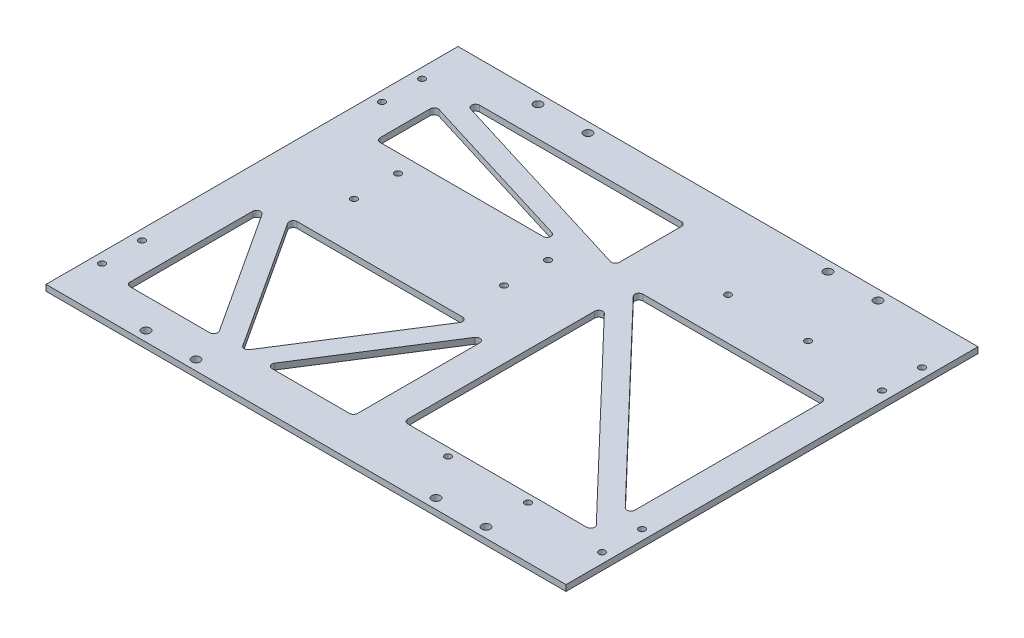
SolidWorks part; units mm, degrees
material "环氧树脂FR-4"
ref_plane "前视基准面" through (0, 0, 0) normal (0, 0, 1) x (1, 0, 0)
ref_plane "上视基准面" through (0, 0, 0) normal (0, 1, 0) x (1, 0, 0)
ref_plane "右视基准面" through (0, 0, 0) normal (1, 0, 0) x (0, 0, -1)
sketch "草图1" plane through (0, 0, 0) normal (0, 1, 0) x (1, 0, 0)
  line L1 (-130, 206) -> (130, 206)
  line L2 (-130, 206) -> (-130, 0)
  line L3 (-130, 0) -> (130, 0)
  line L4 (130, 206) -> (130, 0)
  dimension "D1" = 206
  dimension "D2" = 260
  dimension "D3" = 0
  dimension "D4" = 130
extrude "凸台-拉伸1" add sketch "草图1" along normal blind 3
sketch "草图2" plane through (0, 0, 0) normal (0, -1, 0) x (1, 0, 0)
  line L0 (-130, -206) -> (-130, 0) construction
  line L1 (130, -206) -> (-130, -206) construction
  point P0 (-90, -136)
  point P4 (-15, -136)
  point P7 (-90, -114)
  point P8 (-15, -114)
  dimension "D1" = 40
  dimension "D2" = 70
  dimension "D4" = 75
  dimension "D6" = 22
  dimension "D3" = 2
  dimension "D5" = 2
ref_plane "基准面1" through (0, 0, -103) normal (0, 0, 1) x (1, 0, 0)
hole_wizard "Ø3.2 (3.2) 直径孔1" positions "3D草图1" profile "草图3" hole size "Ø3.2" standard "GB" end condition through all
sketch3d "3D草图1"
  point P0 (-15, 0, -136)
  point P3 (-15, 0, -114)
  point P6 (-90, 0, -136)
  point P9 (-90, 0, -114)
sketch "草图3" plane through (-15, 0, -136) normal (1, 0, 0) x (0, 0, -1)
  line L0 (0, 0) -> (0, 3)
  line L1 (0, 3) -> (1.6, 3)
  line L2 (1.6, 3) -> (1.6, 0)
  line L5 (1.6, 0) -> (0, 0)
  line L11 (0, -6.35) -> (0, 107.95) construction
  dimension "通孔孔直径" = 3.2
  dimension "通孔孔深度" = 3
sketch "草图4" plane through (0, 0, 0) normal (0, -1, 0) x (1, 0, 0)
  line L0 (130, 0) -> (130, -206) construction
  line L1 (130, -206) -> (-130, -206) construction
  point P0 (85, -166)
  point P5 (45, -166)
  point P7 (85, -26)
  point P8 (45, -26)
  dimension "D1" = 45
  dimension "D2" = 40
  dimension "D4" = 40
  dimension "D6" = 140
  dimension "D3" = 2
  dimension "D5" = 2
hole_wizard "Ø3.2 (3.2) 直径孔2" positions "3D草图2" profile "草图5" hole size "Ø3.2" standard "GB" end condition through all
sketch3d "3D草图2"
  point P0 (45, 0, -26)
  point P3 (85, 0, -26)
  point P6 (45, 0, -166)
  point P9 (85, 0, -166)
sketch "草图5" plane through (45, 0, -26) normal (1, 0, 0) x (0, 0, -1)
  line L0 (0, 0) -> (0, 3)
  line L1 (0, 3) -> (1.6, 3)
  line L2 (1.6, 3) -> (1.6, 0)
  line L5 (1.6, 0) -> (0, 0)
  line L11 (0, -6.35) -> (0, 107.95) construction
  dimension "通孔孔直径" = 3.2
  dimension "通孔孔深度" = 3
sketch "草图6" plane through (0, 0, 0) normal (0, -1, 0) x (1, 0, 0)
  line L0 (-130, -206) -> (-130, 0) construction
  line L2 (0, -55) -> (0, 55) construction
  line L4 (1.65, -103) -> (-1.65, -103) construction
  point P0 (-125, -183)
  point P6 (-125, -163)
  point P8 (125, -163)
  point P9 (125, -183)
  point P11 (125, -23)
  point P12 (125, -43)
  point P16 (-125, -43)
  point P17 (-125, -23)
  dimension "D1" = 5
  dimension "D2" = 60
  dimension "D4" = 20
  dimension "D3" = 2
hole_wizard "Ø3.2 (3.2) 直径孔4" positions "3D草图4" profile "草图8" hole size "Ø3.2" standard "GB" end condition through all
sketch3d "3D草图4"
  point P0 (-125, 0, -23)
  point P3 (-125, 0, -43)
  point P6 (-125, 0, -163)
  point P9 (-125, 0, -183)
  point P12 (125, 0, -163)
  point P15 (125, 0, -183)
  point P18 (125, 0, -43)
  point P21 (125, 0, -23)
sketch "草图8" plane through (-125, 0, -23) normal (1, 0, 0) x (0, 0, -1)
  line L0 (0, 0) -> (0, 3)
  line L1 (0, 3) -> (1.6, 3)
  line L2 (1.6, 3) -> (1.6, 0)
  line L5 (1.6, 0) -> (0, 0)
  line L11 (0, -6.35) -> (0, 107.95) construction
  dimension "通孔孔直径" = 3.2
  dimension "通孔孔深度" = 3
sketch "草图9" plane through (0, 0, 0) normal (0, -1, 0) x (1, 0, 0)
  line L0 (130, -206) -> (-130, -206) construction
  point P0 (-60, -201)
  point P3 (-85, -201)
  dimension "D1" = 5
  dimension "D3" = 60
  dimension "D4" = 25
  dimension "D2" = 2
hole_wizard "Ø4.2 (4.2) 直径孔1" positions "3D草图5" profile "草图10" hole size "Ø4.2" standard "GB" end condition through all
sketch3d "3D草图5"
  point P0 (-60, 0, -201)
  point P3 (-85, 0, -201)
sketch "草图10" plane through (-60, 0, -201) normal (1, 0, 0) x (0, 0, -1)
  line L0 (0, 0) -> (0, 3)
  line L1 (0, 3) -> (2.1, 3)
  line L2 (2.1, 3) -> (2.1, 0)
  line L5 (2.1, 0) -> (0, 0)
  line L11 (0, -6.35) -> (0, 107.95) construction
  dimension "通孔孔直径" = 4.2
  dimension "通孔孔深度" = 3
mirror "镜向1" about plane through (0, 0, 0) normal (1, 0, 0) of "Ø4.2 (4.2) 直径孔1"
mirror "镜向2" about plane through (0, 0, -103) normal (0, 0, 1) of "Ø4.2 (4.2) 直径孔1", "镜向1"
sketch "草图11" plane through (0, 0, 0) normal (0, -1, 0) x (1, 0, 0)
  line L0 (-110, -20) -> (-110, -90)
  line L1 (-110, -90) -> (-64.4321, -20)
  line L2 (-64.4321, -20) -> (-110, -20)
  line L3 (-52.5, -20) -> (-98.0679, -90)
  line L4 (-98.0679, -90) -> (-8.0679, -90)
  line L5 (-8.0679, -90) -> (-52.5, -20)
  line L6 (-40.6556, -20) -> (3.7766, -90)
  line L7 (3.7766, -90) -> (3.7766, -20)
  line L8 (3.7766, -20) -> (-40.6556, -20)
  line L9 (-130, -206) -> (-130, 0) construction
  line L10 (-130, 0) -> (130, 0) construction
  line L20 (18.7766, -145) -> (115, -145)
  line L41 (130, -206) -> (-130, -206) construction
  line L42 (-110, -145) -> (-13.2289, -145)
  line L43 (-110, -145) -> (-110, -174.7688)
  line L44 (-112.4991, -186) -> (3.7766, -186)
  line L45 (3.7766, -150.2312) -> (3.7766, -186)
  line L46 (-112.4991, -186) -> (3.7766, -150.2312)
  line L47 (-110, -174.7688) -> (-13.2289, -145)
  line L48 (18.7766, -30) -> (18.7766, -130.5374)
  line L49 (18.7766, -130.5374) -> (115, -30)
  line L51 (115, -30) -> (18.7766, -30)
  line L52 (130, 0) -> (130, -206) construction
  line L53 (18.7766, -145) -> (115, -44.4626)
  line L59 (115, -145) -> (115, -44.4626)
  circle A2 centre (-90, -114) radius 1.6 construction
  point P18 (65, -91.593)
  point P28 (56.9254, -85.6937)
  point P29 (101.9254, -24.1007)
  point P38 (-112.9402, -170.442)
  point P39 (0.8363, -135.442)
  point P42 (-111.4701, -175.221)
  point P43 (2.3064, -140.221)
  dimension "D7" = 37.5
  dimension "D1" = 20
  dimension "D2" = 20
  dimension "D3" = 20
  dimension "D4" = 0
  dimension "D5" = 70
  dimension "D6" = 10
  dimension "D8" = 0
  dimension "D9" = 10
  dimension "D10" = 113.7766
  dimension "D11" = 90
  dimension "D12" = 15
  dimension "D13" = 15
  dimension "D14" = 30
  dimension "D15" = 0
  dimension "D16" = 10
  dimension "D17" = 0
  dimension "D18" = 15
  dimension "D23" = 20
  dimension "D24" = 20
  dimension "D25" = 0
  dimension "D26" = 96.7711
  dimension "D27" = 10
  dimension "D28" = 29.7688
  dimension "D29" = 55
extrude "切除-拉伸1" cut sketch "草图11" against normal through all
fillet "圆角1" radius 2 21 edges at (-110, 1.5, -145) (-13.2289, 1.5, -145) (-110, 1.5, -174.7688) (-112.4991, 1.5, -186) (3.7766, 1.5, -150.2312) (3.7766, 1.5, -186) (-110, 1.5, -90) (-98.0679, 1.5, -90) (-8.0679, 1.5, -90) (3.7766, 1.5, -90) (18.7766, 1.5, -130.5374) (18.7766, 1.5, -145) (115, 1.5, -145) (115, 1.5, -44.4626) (115, 1.5, -30) (18.7766, 1.5, -30) (3.7766, 1.5, -20) (-40.6556, 1.5, -20) (-52.5, 1.5, -20) (-64.4321, 1.5, -20) (-110, 1.5, -20)
